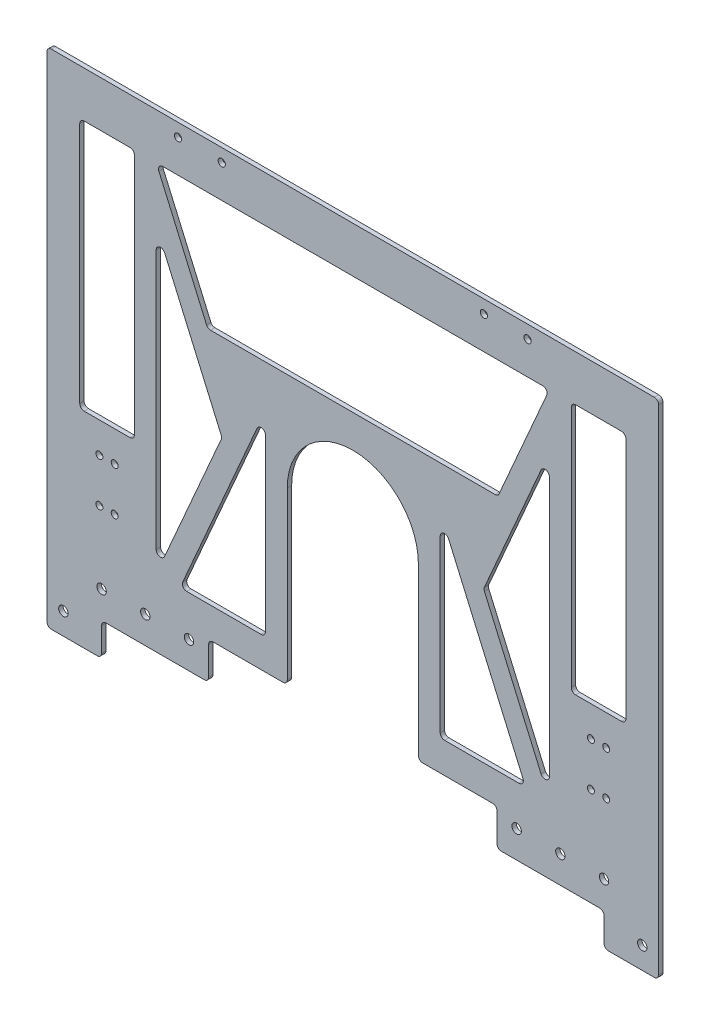
SolidWorks part; units mm, degrees
material "环氧板"
ref_plane "前视基准面" through (0, 0, 0) normal (0, 0, 1) x (1, 0, 0)
ref_plane "上视基准面" through (0, 0, 0) normal (0, 1, 0) x (1, 0, 0)
ref_plane "右视基准面" through (0, 0, 0) normal (1, 0, 0) x (0, 0, -1)
other "Configuration Table"
sketch "草图1" plane through (0, 0, 0) normal (0, 0, 1) x (1, 0, 0)
  line L1 (-140, 115) -> (140, 115)
  line L2 (-140, 115) -> (-140, -115)
  line L3 (-140, -115) -> (140, -115)
  line L4 (140, 115) -> (140, -115)
  line L5 (-140, 115) -> (140, -115) construction
  line L6 (-140, -115) -> (140, 115) construction
  point P0 (0, 0)
  dimension "D1" = 280
  dimension "D2" = 230
extrude "凸台-拉伸1" add sketch "草图1" along normal blind 2
sketch "草图2" plane through (0, 0, 2) normal (0, 0, 1) x (1, 0, 0)
  line L0 (-140, -115) -> (140, -115) construction
  line L1 (-140, 115) -> (-140, -115) construction
  line L2 (0, 0) -> (0, -147.9054) construction
  line L3 (-115, -87.5) -> (-95, -87.5) construction
  circle A0 centre (-132.5, -105) radius 2.15
  circle A1 centre (132.5, -105) radius 2.15
  circle A2 centre (-115, -87.5) radius 2.15
  circle A3 centre (-95, -87.5) radius 2.15
  circle A4 centre (-75, -87.5) radius 2.15
  circle A5 centre (75, -87.5) radius 2.15
  circle A6 centre (95, -87.5) radius 2.15
  circle A7 centre (115, -87.5) radius 2.15
  dimension "D1" = 10
  dimension "D2" = 7.5
  dimension "D3" = 4.3
  dimension "D4" = 17.5
  dimension "D5" = 3
  dimension "17.5" = 17.5
  dimension "D6" = 20
extrude "切除-拉伸1" cut sketch "草图2" against normal through all
sketch "草图3" plane through (0, 0, 2) normal (0, 0, 1) x (1, 0, 0)
  line L0 (-140, -115) -> (140, -115) construction
  line L1 (-30, -5) -> (-30, -115)
  line L2 (30, -5) -> (30, -115)
  line L3 (30, -115) -> (-30, -115)
  circle A0 centre (0, -5) radius 30
  line M12 (-140, -115) -> (140, -115)
  dimension "D1" = 110
  dimension "D2" = 60
extrude "切除-拉伸2" cut sketch "草图3" against normal through all contours A0 | A0 L1 L2 M12
sketch "草图4" plane through (0, 0, 2) normal (0, 0, 1) x (1, 0, 0)
  line L0 (-140, 115) -> (-140, -115) construction
  line L1 (-140, -115) -> (-30, -115) construction
  line L2 (-109, -35) -> (-116, -35) construction
  line L3 (0, 0) -> (0, -99.1483) construction
  circle A0 centre (-109, -35) radius 1.6
  circle A1 centre (-109, -55) radius 1.6
  circle A2 centre (-116, -35) radius 1.6
  circle A3 centre (-116, -55) radius 1.6
  circle A4 centre (116, -55) radius 1.6
  circle A5 centre (116, -35) radius 1.6
  circle A6 centre (109, -55) radius 1.6
  circle A7 centre (109, -35) radius 1.6
  dimension "D1" = 3.2
  dimension "D2" = 20
  dimension "D4" = 60
  dimension "D3" = 31
  dimension "D6" = 7
  dimension "D5" = 2
extrude "切除-拉伸3" cut sketch "草图4" against normal through all
sketch "草图5" plane through (0, 0, 2) normal (0, 0, 1) x (1, 0, 0)
  line L0 (140, 115) -> (-140, 115) construction
  line L1 (-140, 115) -> (-140, -115) construction
  line L2 (0, 0) -> (0, 162.8227) construction
  line L3 (140, -115) -> (140, 115) construction
  line L4 (30, -115) -> (140, -115) construction
  line L5 (-140, -115) -> (-30, -115) construction
  circle A0 centre (-60, 109) radius 1.65
  circle A1 centre (-80, 109) radius 1.65
  circle A2 centre (80, 109) radius 1.65
  circle A3 centre (60, 109) radius 1.65
  dimension "D1" = 6
  dimension "D2" = 3.3
  dimension "D3" = 20
  dimension "D4" = 60
extrude "切除-拉伸4" cut sketch "草图5" against normal through all
sketch "草图6" plane through (0, 0, 2) normal (0, 0, 1) x (1, 0, 0)
  circle A0 centre (0, 0) radius 104 construction
  dimension "D1" = 208
sketch "草图7" plane through (0, 0, 2) normal (0, 0, 1) x (1, 0, 0)
  line L0 (-90, 69) -> (-90, -69)
  line L1 (-90, -69) -> (-59.8859, 0)
  line L2 (-59.8859, 0) -> (-90, 69)
  line L3 (0, 0) -> (0, -89.6558) construction
  line L4 (-90, 94) -> (-66.4325, 40)
  line L7 (66.4325, 40) -> (90, 94)
  line L8 (90, 94) -> (-90, 94)
  line L9 (-66.4325, 40) -> (66.4325, 40)
  line L10 (-140, 115) -> (-140, -115) construction
  line L11 (-40, 20.5644) -> (-79.0891, -69)
  line L12 (-79.0891, -69) -> (-40, -69)
  line L13 (-40, -69) -> (-40, 20.5644)
  line L14 (-30, -5) -> (-30, -115) construction
  line L15 (40, -69) -> (40, 20.5644)
  line L16 (79.0891, -69) -> (40, -69)
  line L17 (40, 20.5644) -> (79.0891, -69)
  line L18 (59.8859, 0) -> (90, 69)
  line L19 (90, -69) -> (59.8859, 0)
  line L20 (90, 69) -> (90, -69)
  line L21 (100, 94) -> (100, -21)
  line L22 (-125, 94) -> (-100, 94)
  line L23 (-125, 94) -> (-125, -21)
  line L24 (-125, -21) -> (-100, -21)
  line L25 (-100, 94) -> (-100, -21)
  line L26 (125, -21) -> (100, -21)
  line L27 (125, 94) -> (125, -21)
  line L28 (125, 94) -> (100, 94)
  line L29 (115, -115) -> (115, -100)
  line L30 (-30, -115) -> (-115, -115)
  line L31 (-30, -115) -> (-30, -100)
  line L32 (-30, -100) -> (-115, -100)
  line L33 (-115, -115) -> (-115, -100)
  line L34 (30, -100) -> (115, -100)
  line L35 (30, -115) -> (30, -100)
  line L36 (30, -115) -> (115, -115)
  circle A0 centre (60, 109) radius 1.65 construction
  dimension "D1" = 15
  dimension "D2" = 10
  dimension "D3" = 25
  dimension "D4" = 40
  dimension "D5" = 50
  dimension "D6" = 10
  dimension "D7" = 10
  dimension "D8" = 10
  dimension "D9" = 15
  dimension "D10" = 115
  dimension "D11" = 85
  dimension "D12" = 15
extrude "切除-拉伸5" cut sketch "草图7" against normal through all
sketch "草图9" plane through (0, 0, 2) normal (0, 0, 1) x (1, 0, 0)
  line L0 (0, 0) -> (0, -134.4577) construction
  line L1 (66, -100) -> (66, -83)
  line L2 (-30, -100) -> (-66, -100)
  line L3 (-30, -100) -> (-30, -83)
  line L4 (-30, -83) -> (-66, -83)
  line L5 (-66, -100) -> (-66, -83)
  line L6 (30, -83) -> (66, -83)
  line L7 (30, -100) -> (30, -83)
  line L8 (30, -100) -> (66, -100)
  dimension "D1" = 17
  dimension "D2" = 36
extrude "切除-拉伸6" cut sketch "草图9" against normal through all
fillet "圆角1" radius 2 24 edges at (-90, -69, 1) (125, -21, 1) (100, -21, 1) (100, 94, 1) (125, 94, 1) (90, 69, 1) (90, -69, 1) (59.8859, 0, 1) (-100, 94, 1) (-100, -21, 1) (-125, -21, 1) (-125, 94, 1) (-90, 94, 1) (90, 94, 1) (66.4325, 40, 1) (-66.4325, 40, 1) (-40, 20.5644, 1) (-40, -69, 1) (-79.0891, -69, 1) (40, 20.5644, 1) (79.0891, -69, 1) (40, -69, 1) (-90, 69, 1) (-59.8859, 0, 1)
fillet "圆角2" radius 2 14 edges at (-115, -100, 1) (-115, -115, 1) (-140, -115, 1) (140, 115, 1) (140, -115, 1) (115, -115, 1) (115, -100, 1) (-140, 115, 1) (66, -100, 1) (66, -83, 1) (30, -83, 1) (-66, -100, 1) (-30, -83, 1) (-66, -83, 1)
